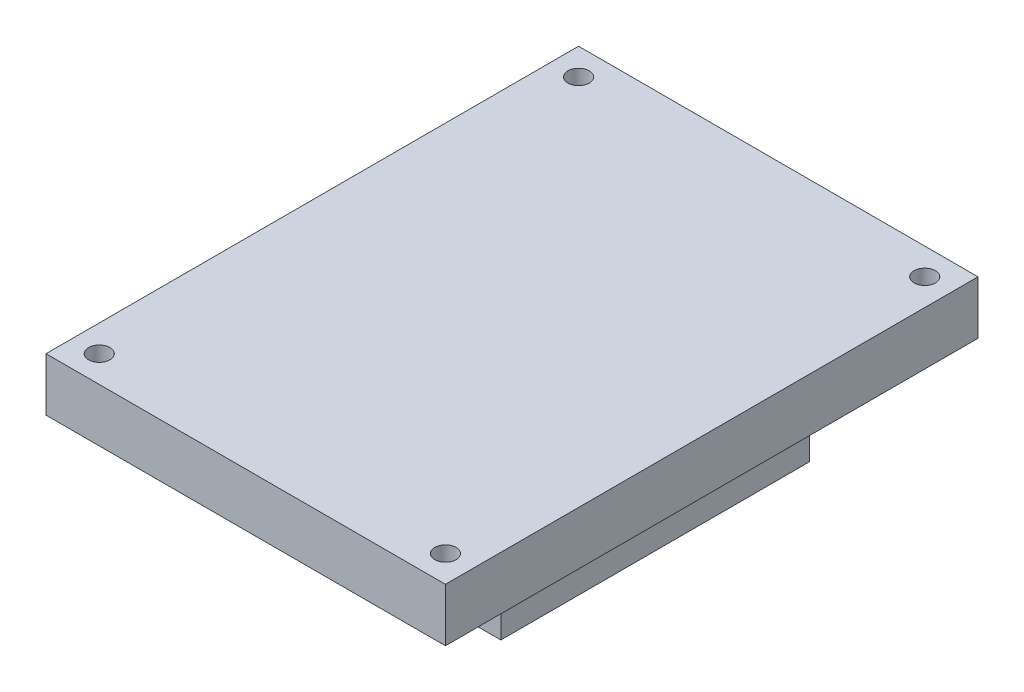
SolidWorks part; units mm, degrees
ref_plane "Front Plane" through (0, 0, 0) normal (0, 0, 1) x (1, 0, 0)
ref_plane "Top Plane" through (0, 0, 0) normal (0, 1, 0) x (1, 0, 0)
ref_plane "Right Plane" through (0, 0, 0) normal (1, 0, 0) x (0, 0, -1)
sketch "Sketch1" plane through (0, 0, 0) normal (0, 1, 0) x (1, 0, 0)
  line L1 (37.5, -50) -> (-37.5, -50)
  line L2 (37.5, -50) -> (37.5, 50)
  line L3 (37.5, 50) -> (-37.5, 50)
  line L4 (-37.5, -50) -> (-37.5, 50)
  line L5 (37.5, -50) -> (-37.5, 50) construction
  line L6 (37.5, 50) -> (-37.5, -50) construction
  point P0 (0, 0)
  dimension "D1" = 100
  dimension "D2" = 75
extrude "Boss-Extrude1" add sketch "Sketch1" along normal blind 10
sketch "Sketch2" plane through (0, 0, 0) normal (0, -1, 0) x (1, 0, 0)
  line L0 (-10, 7.8498) -> (-10, -31.6502) construction
  line L1 (-15, 17.0998) -> (15, 17.0998)
  line L2 (-15, 17.0998) -> (-15, -40.9002)
  line L3 (-15, -40.9002) -> (15, -40.9002)
  line L4 (15, 17.0998) -> (15, -40.9002)
  line L5 (10, -31.6502) -> (10, 7.8498) construction
  line L6 (-3.3, -38.9002) -> (3.3, -38.9002) construction
  line L7 (-3.3, 15.0998) -> (3.3, 15.0998) construction
  line L8 (-9.3, -32.3502) -> (9.3, -32.3502) construction
  line L9 (-10, 8.5498) -> (10, 8.5498)
  line L10 (-10, 8.5498) -> (-10, -32.3502)
  line L11 (-10, -32.3502) -> (10, -32.3502)
  line L12 (10, 8.5498) -> (10, -32.3502)
  line L13 (9.3, 8.5498) -> (-9.3, 8.5498) construction
  dimension "D1" = 5
  dimension "D2" = 5
  dimension "D3" = 2
  dimension "D4" = 2
  dimension "D5" = 0
  dimension "D6" = 0
  dimension "D7" = 0
  dimension "D8" = 0
extrude "Boss-Extrude2" add sketch "Sketch2" along normal up to vertex (26.76 mm away)
sketch "Sketch3" plane through (0, -26.76, 0) normal (0, -1, 0) x (1, 0, 0)
  circle A0 centre (-5, 12.3998) radius 2
  circle A1 centre (5, 12.3998) radius 2
  circle A2 centre (5, -36.2002) radius 2
  circle A3 centre (-5, -36.2002) radius 2
extrude "Cut-Extrude1" cut sketch "Sketch3" against normal blind 3
sketch "Sketch4" plane through (0, 0, 0) normal (0, -1, 0) x (1, 0, 0)
  line L0 (0, -39.05) -> (0, 39.05) construction
  line L1 (39.05, 0) -> (-39.05, 0) construction
  circle A0 centre (-32.5, -45) radius 2
  circle A1 centre (32.5, -45) radius 2
  circle A2 centre (32.5, 45) radius 2
  circle A3 centre (-32.5, 45) radius 2
  dimension "D2" = 4
extrude "Cut-Extrude2" cut sketch "Sketch4" against normal blind 23
